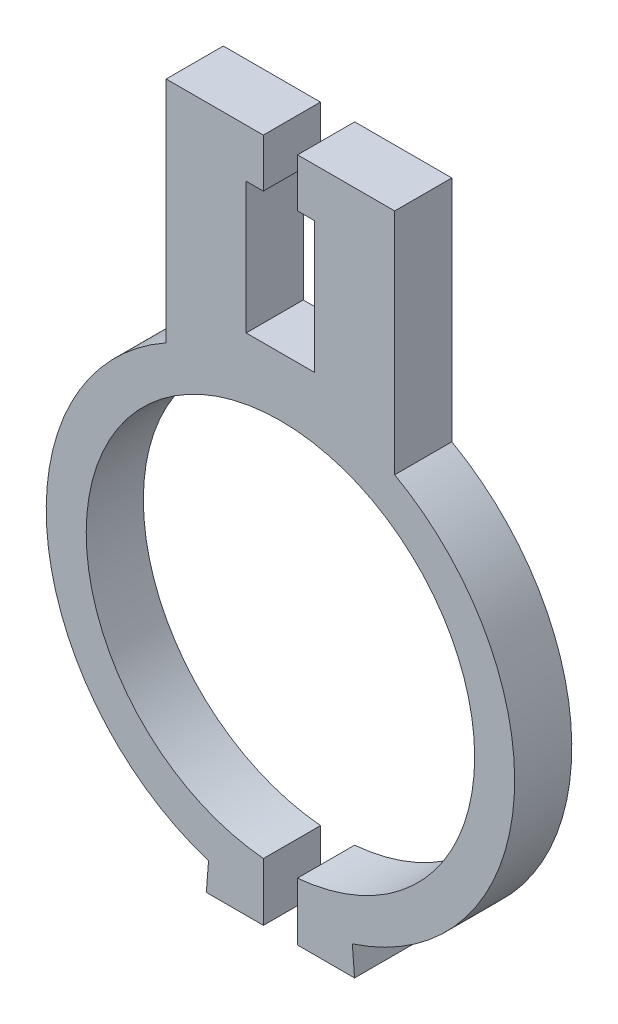
SolidWorks part; units mm, degrees
ref_plane "Alzado" through (0, 0, 0) normal (0, 0, 1) x (1, 0, 0)
ref_plane "Planta" through (0, 0, 0) normal (0, 1, 0) x (1, 0, 0)
ref_plane "Vista lateral" through (0, 0, 0) normal (1, 0, 0) x (0, 0, -1)
sketch "Croquis1" plane through (0, 0, 0) normal (0, 0, 1) x (1, 0, 0)
  line L0 (0, -34) -> (0, 34) construction
  line L1 (-20, 35.7911) -> (-20, 75.7911)
  line L2 (-20, 75.7911) -> (-3, 75.7911)
  line L3 (-3, 75.7911) -> (-3, 67.2911)
  line L4 (-3, 67.2911) -> (-6, 67.2911)
  line L5 (-6, 67.2911) -> (-6, 44.2911)
  line L6 (-6, 44.2911) -> (-3, 44.2911)
  line L9 (6, 44.2911) -> (3, 44.2911)
  line L10 (6, 67.2911) -> (6, 44.2911)
  line L11 (3, 67.2911) -> (6, 67.2911)
  line L12 (3, 75.7911) -> (3, 67.2911)
  line L13 (20, 75.7911) -> (3, 75.7911)
  line L14 (20, 35.7911) -> (20, 75.7911)
  line L15 (-12.5813, -39.0219) -> (-12.975, -44.0064)
  line L16 (-12.975, -44.0064) -> (-2.975, -44.0064)
  line L17 (-2.975, -44.0064) -> (-2.975, -40.8919)
  line L18 (2.975, -44.0064) -> (2.975, -40.8919)
  line L19 (12.5813, -39.0219) -> (12.975, -44.0064)
  line L20 (12.975, -44.0064) -> (2.975, -44.0064)
  line L21 (-2.975, -40.8919) -> (-2.975, -33.8696)
  line L22 (2.975, -40.8919) -> (2.975, -33.8696)
  line L23 (0, 41) -> (0, 20089.5291) construction
  line L24 (-3, 44.2911) -> (3, 44.2911)
  arc A0 (2.975, -33.8696) -> (-2.975, -33.8696) centre (0, 0) ccw
  arc A1 (-20, 35.7911) -> (-12.5813, -39.0219) centre (0, 0) ccw
  arc A4 (12.5813, -39.0219) -> (20, 35.7911) centre (0, 0) ccw
  point P13 (-6, 55.7911)
  point P15 (-20, 55.7911)
  dimension "D1" = 68
  dimension "D2" = 82
  dimension "D3" = 40
  dimension "D4" = 23
  dimension "D5" = 12
  dimension "D6" = 3
  dimension "D7" = 20
  dimension "D8" = 5
  dimension "D9" = 10
extrude "Saliente-Extruir1" add sketch "Croquis1" along normal blind 10
